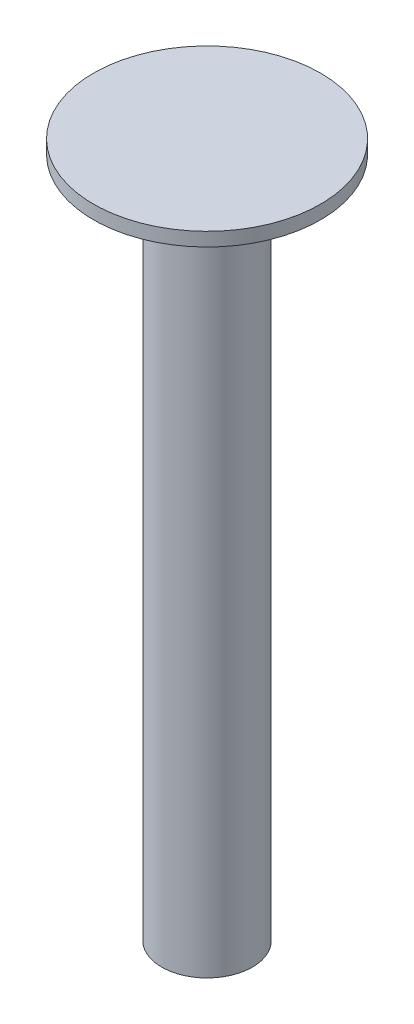
SolidWorks part; units mm, degrees
material "Plain Carbon Steel"
ref_plane "Front Plane" through (0, 0, 0) normal (0, 0, 1) x (1, 0, 0)
ref_plane "Top Plane" through (0, 0, 0) normal (0, 1, 0) x (1, 0, 0)
ref_plane "Right Plane" through (0, 0, 0) normal (1, 0, 0) x (0, 0, -1)
sketch "Sketch1" plane through (0, 0, 0) normal (0, 1, 0) x (1, 0, 0)
  circle A0 centre (0, 0) radius 5.08
  dimension "D1" = 10.16
extrude "Boss-Extrude1" add sketch "Sketch1" along normal blind 76.2 contours A0
sketch "Sketch2" plane through (0, 76.2, 0) normal (0, 1, 0) x (1, 0, 0)
  circle A0 centre (0, 0) radius 12.7
  dimension "D1" = 25.4
extrude "Boss-Extrude2" add sketch "Sketch2" along normal blind 1.524
